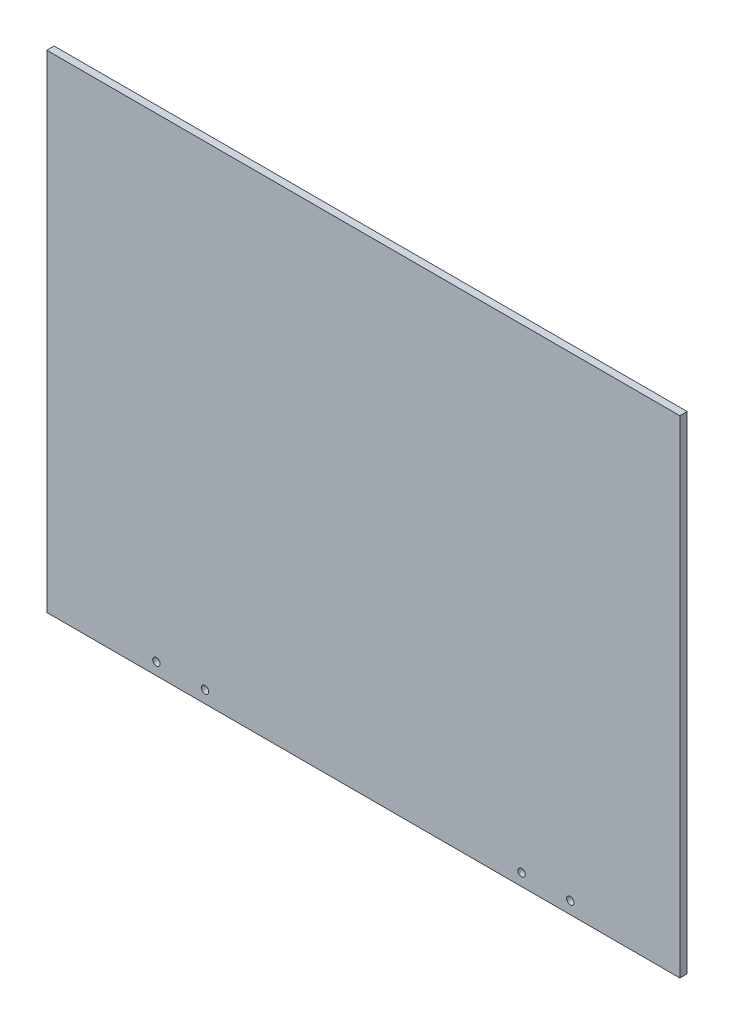
SolidWorks part; units mm, degrees
ref_plane "Front Plane" through (0, 0, 0) normal (0, 0, 1) x (1, 0, 0)
ref_plane "Top Plane" through (0, 0, 0) normal (0, 1, 0) x (1, 0, 0)
ref_plane "Right Plane" through (0, 0, 0) normal (1, 0, 0) x (0, 0, -1)
sketch "Sketch1" plane through (0, 0, 0) normal (0, 0, 1) x (1, 0, 0)
  line L0 (0, -100) -> (0, 0) construction
  line L1 (-130, 100) -> (130, 100)
  line L2 (-130, 100) -> (-130, -100)
  line L3 (-130, -100) -> (130, -100)
  line L4 (130, 100) -> (130, -100)
  line L5 (-130, 100) -> (130, -100) construction
  line L6 (-130, -100) -> (130, 100) construction
  line L7 (0, -100) -> (0, -97.5) construction
  point P0 (0, 0)
extrude "Boss-Extrude1" add sketch "Sketch1" along normal blind 3
sketch "Sketch2" plane through (0, 0, 3) normal (0, 0, 1) x (1, 0, 0)
  line L0 (0, -95) -> (-65, -95) construction
  line L1 (-65, -95) -> (-85, -95) construction
  line L3 (0, -95) -> (0, -100) construction
  line L4 (-130, -100) -> (130, -100) construction
  circle A0 centre (-65, -95) radius 1.5
  circle A1 centre (-85, -95) radius 1.5
  circle A4 centre (85, -95) radius 1.5
  circle A5 centre (65, -95) radius 1.5
  dimension "D1" = 65
  dimension "D2" = 20
  dimension "D3" = 5
extrude "Cut-Extrude1" cut sketch "Sketch2" against normal through all both and the other way through all
